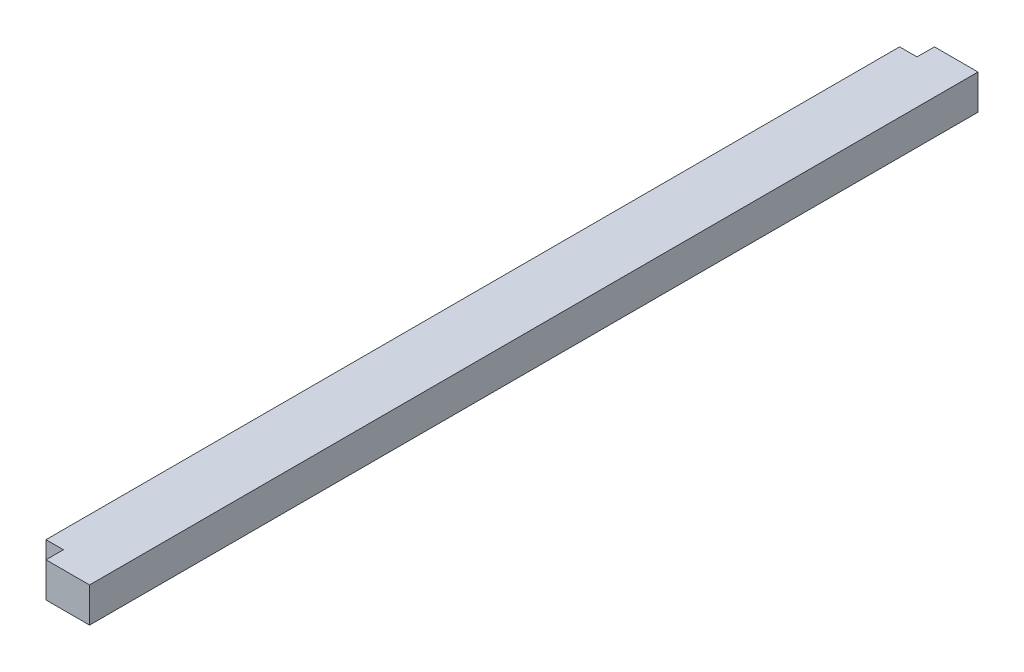
SolidWorks part; units mm, degrees
material "Сосна"
ref_plane "Спереди" through (0, 0, 0) normal (0, 0, 1) x (1, 0, 0)
ref_plane "Сверху" through (0, 0, 0) normal (0, 1, 0) x (1, 0, 0)
ref_plane "Справа" through (0, 0, 0) normal (1, 0, 0) x (0, 0, -1)
sketch "Эскиз1" plane through (0, 0, 0) normal (0, 0, -1) x (1, 0, 0)
  line L0 (0, 10) -> (10, 10)
  line L1 (0, 0) -> (35, 0)
  line L2 (0, 0) -> (0, 10)
  line L3 (10, 20) -> (35, 20)
  line L4 (35, 0) -> (35, 20)
  line L5 (10, 10) -> (10, 20)
  dimension "D1" = 35
  dimension "D2" = 20
  dimension "D3" = 10
  dimension "D4" = 10
extrude "Бобышка-Вытянуть1" add sketch "Эскиз1" along normal blind 510
sketch "Эскиз2" plane through (0, 0, 0) normal (0, 1, 0) x (1, 0, 0)
  line L0 (35, 255) -> (0, 255) construction
  line L1 (0, 500) -> (10, 500)
  line L2 (0, 500) -> (0, 510)
  line L3 (0, 510) -> (10, 510)
  line L4 (10, 500) -> (10, 510)
  line L5 (35, 510) -> (35, 0) construction
  line L6 (0, 510) -> (0, 0) construction
  line L7 (10, 10) -> (10, 0)
  line L8 (0, 0) -> (10, 0)
  line L9 (0, 10) -> (0, 0)
  line L10 (0, 10) -> (10, 10)
  dimension "D1" = 10
  dimension "D2" = 10
extrude "Вырез-Вытянуть1" cut sketch "Эскиз2" against normal through all
